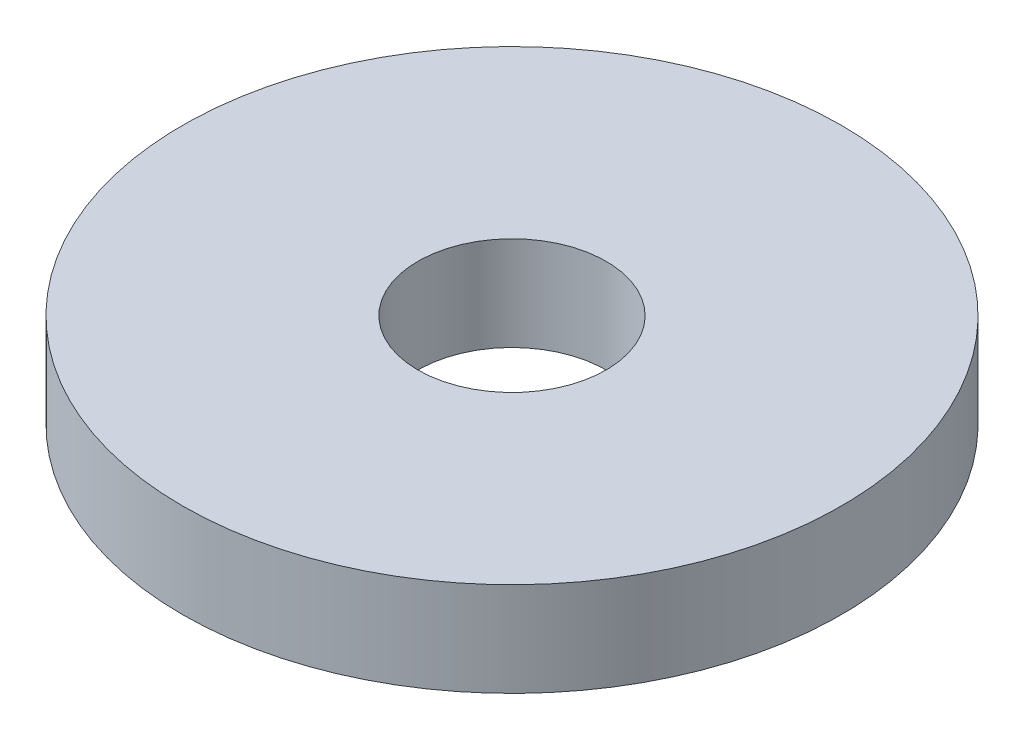
SolidWorks part; units mm, degrees
ref_plane "Front Plane" through (0, 0, 0) normal (0, 0, 1) x (1, 0, 0)
ref_plane "Top Plane" through (0, 0, 0) normal (0, 1, 0) x (1, 0, 0)
ref_plane "Right Plane" through (0, 0, 0) normal (1, 0, 0) x (0, 0, -1)
sketch "Sketch1" plane through (0, 0, 0) normal (0, 1, 0) x (1, 0, 0)
  circle A0 centre (0, 0) radius 4 construction
  circle A1 centre (0, 0) radius 7
  circle A2 centre (0, 0) radius 2
  dimension "D1" = 14
  dimension "D2" = 4
extrude "Boss-Extrude1" add sketch "Sketch1" along normal blind 2
